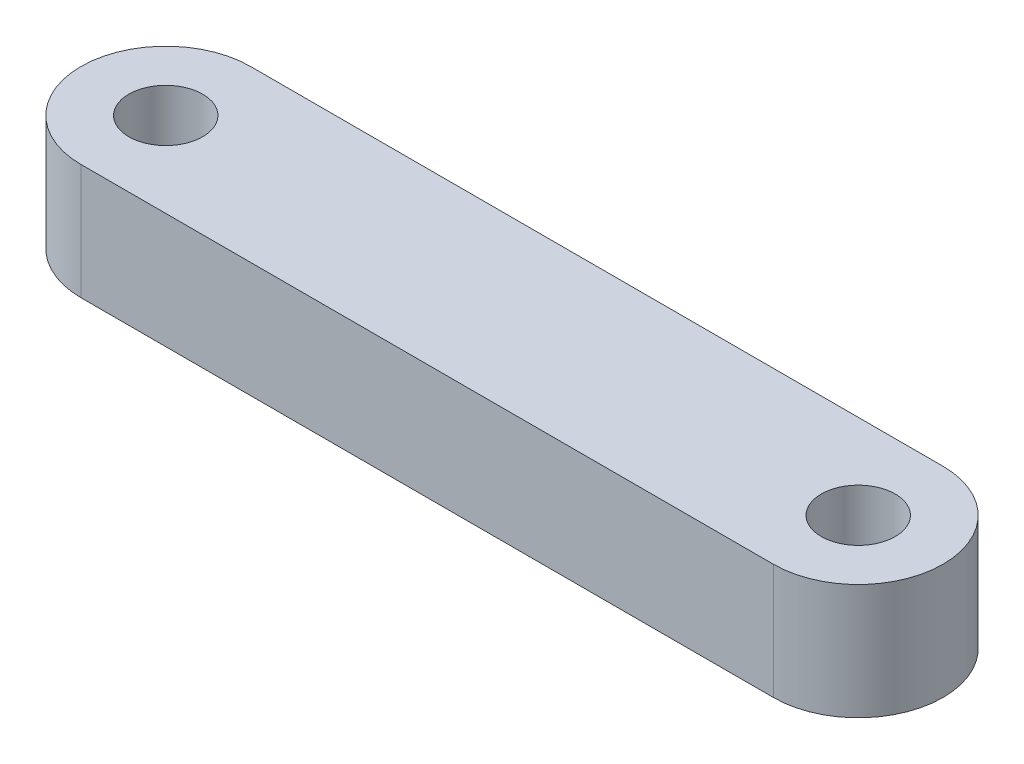
SolidWorks part; units mm, degrees
ref_plane "Front Plane" through (0, 0, 0) normal (0, 0, 1) x (1, 0, 0)
ref_plane "Top Plane" through (0, 0, 0) normal (0, 1, 0) x (1, 0, 0)
ref_plane "Right Plane" through (0, 0, 0) normal (1, 0, 0) x (0, 0, -1)
sketch "Sketch1" plane through (0, 0, 0) normal (0, 1, 0) x (1, 0, 0)
  line L0 (0, 0) -> (-30, 0) construction
  line L1 (0, -3.675) -> (-30, -3.675)
  line L2 (0, 3.675) -> (-30, 3.675)
  arc A0 (0, -3.675) -> (0, 3.675) centre (0, 0) ccw
  arc A1 (-30, 3.675) -> (-30, -3.675) centre (-30, 0) ccw
  circle A2 centre (-30, 0) radius 1.6
  circle A3 centre (0, 0) radius 1.6
  point P3 (-15, 0)
  dimension "D2" = 3.2
  dimension "D3" = 3.2
  dimension "D1" = 30
  dimension "D4" = 7.35
extrude "Boss-Extrude1" add sketch "Sketch1" along normal blind 5
